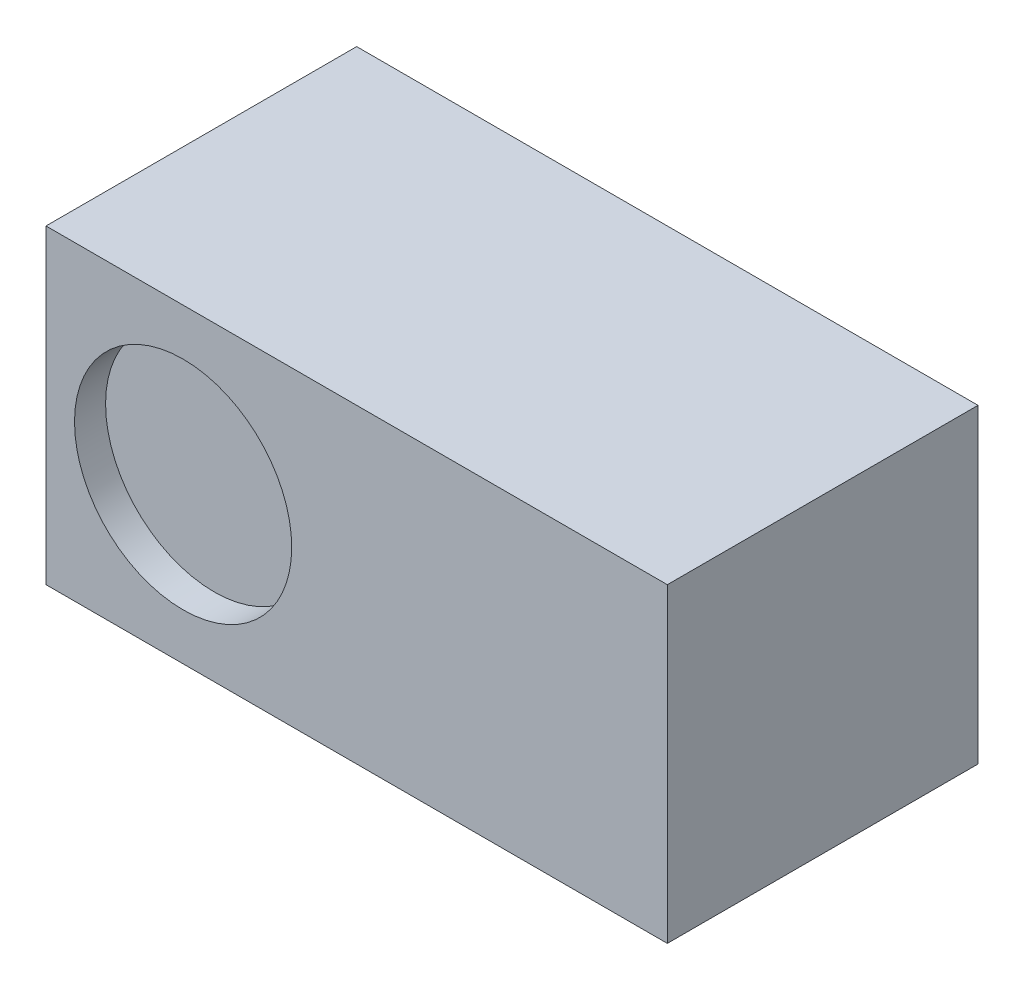
SolidWorks part; units mm, degrees
ref_plane "Front Plane" through (0, 0, 0) normal (0, 0, 1) x (1, 0, 0)
ref_plane "Top Plane" through (0, 0, 0) normal (0, 1, 0) x (1, 0, 0)
ref_plane "Right Plane" through (0, 0, 0) normal (1, 0, 0) x (0, 0, -1)
sketch "Sketch1" plane through (0, 0, 0) normal (0, 0, 1) x (1, 0, 0)
  line L0 (0, 0) -> (0, 8.3017) construction
  line L1 (-25.4, 12.7) -> (25.4, 12.7)
  line L2 (-25.4, 12.7) -> (-25.4, -12.7)
  line L3 (-25.4, -12.7) -> (25.4, -12.7)
  line L4 (25.4, 12.7) -> (25.4, -12.7)
  line L5 (0, 0) -> (11.6554, 0) construction
  dimension "D1" = 25.4
  dimension "D2" = 50.8
extrude "Boss-Extrude1" add sketch "Sketch1" along normal blind 25.4
sketch "Sketch2" plane through (0, 0, 25.4) normal (0, 0, 1) x (1, 0, 0)
  circle A0 centre (-14.1896, 0) radius 8.8792
extrude "Cut-Extrude1" cut sketch "Sketch2" against normal blind 2.54
